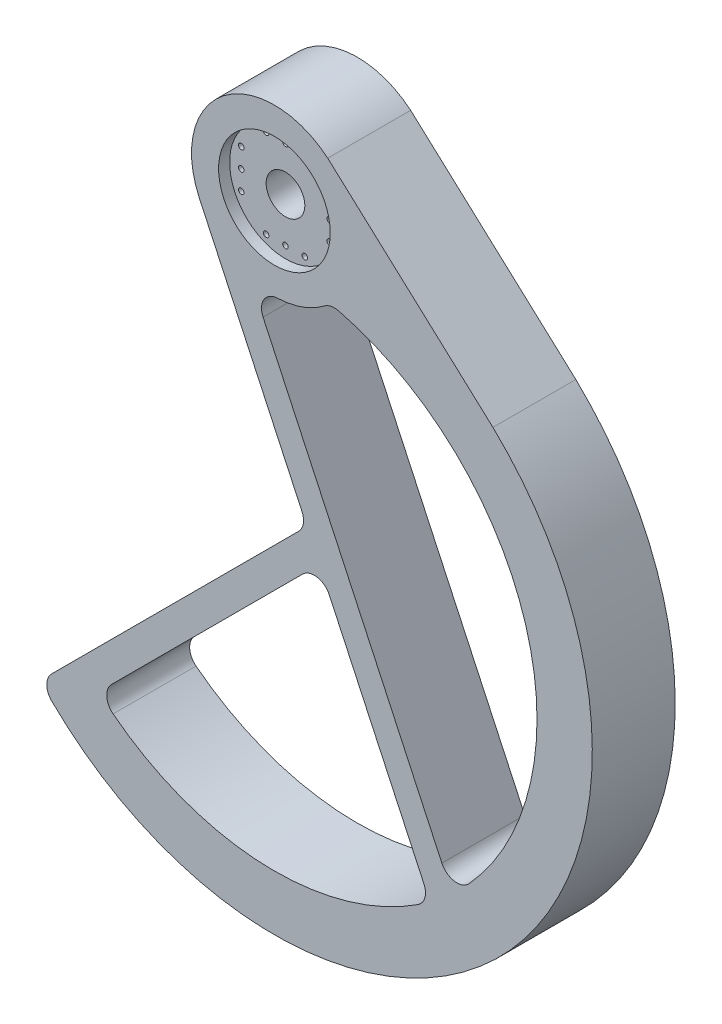
SolidWorks part; units mm, degrees
material "ABS"
ref_plane "正面" through (0, 0, 0) normal (0, 0, 1) x (1, 0, 0)
ref_plane "平面" through (0, 0, 0) normal (0, 1, 0) x (1, 0, 0)
ref_plane "右側面" through (0, 0, 0) normal (1, 0, 0) x (0, 0, -1)
sketch "ｽｹｯﾁ1" plane through (0, 0, 0) normal (0, 0, 1) x (1, 0, 0)
  line L1 (9.9336, 0.7043) -> (27.0462, -35.9938)
  line L2 (9.6418, 68.9907) -> (39.5241, 41.7624)
  line L4 (4.3888, 7.9244) -> (-40.3035, -36.7679)
  line L5 (5.0933, 1.5578) -> (-29.4572, -32.9928)
  line L6 (-13.5946, 51.1607) -> (4.9864, 11.3135)
  line L7 (30.2877, -31.1143) -> (-2.0547, 38.2444)
  arc A0 (-40.2839, -41.0299) -> (37.9168, 43.2269) centre (0, 0) ccw
  arc A1 (-29.1788, -37.4813) -> (25.9673, -39.7737) centre (0, 0) ccw
  arc A2 (0.5535, 42.5102) -> (9.0577, 45.5435) centre (0, 57.5) ccw
  arc A3 (35.2318, -31.8586) -> (11.602, 46.0613) centre (0, 0) ccw
  arc A4 (10.5469, 68.1659) -> (-13.5946, 51.1607) centre (0, 57.5) ccw
  arc A5 (-40.3035, -36.7679) -> (-40.2839, -41.0299) centre (-38.1821, -38.8893) ccw
  arc A6 (-29.4572, -32.9928) -> (-29.1788, -37.4813) centre (-27.3359, -35.1141) ccw
  arc A7 (27.0462, -35.9938) -> (25.9673, -39.7737) centre (24.3273, -37.2617) cw
  arc A8 (5.0933, 1.5578) -> (9.9336, 0.7043) centre (7.2147, -0.5635) cw
  arc A9 (35.2318, -31.8586) -> (30.2877, -31.1143) centre (33.0067, -29.8464) cw
  arc A10 (4.9864, 11.3135) -> (4.3888, 7.9244) centre (2.2675, 10.0457) cw
  arc A11 (-2.0547, 38.2444) -> (0.5535, 42.5102) centre (0.6642, 39.5123) cw
  arc A12 (11.602, 46.0613) -> (9.0577, 45.5435) centre (10.8692, 43.1522) ccw
  point P24 (8.1229, 4.5874)
  dimension "D1" = 3
  dimension "D2" = 3
  dimension "D3" = 3
  dimension "D4" = 3
  dimension "D5" = 3
  dimension "D6" = 3
  dimension "D7" = 3
  dimension "D8" = 3
extrude "ﾎﾞｽ - 押し出し1" add sketch "ｽｹｯﾁ1" along normal blind 15 contours L6 A10 L4 A5 A0 L2 A4 A12 A3 A9 L7 A11 A2 L5 A8 L1 A7 A1 A6
sketch "ｽｹｯﾁ6" plane through (0, 0, 15) normal (0, 0, 1) x (1, 0, 0)
  circle A0 centre (0, 57.5) radius 3.5
extrude "ｶｯﾄ - 押し出し2" cut sketch "ｽｹｯﾁ6" against normal blind 15
sketch "ｽｹｯﾁ7" plane through (0, 0, 15) normal (0, 0, 1) x (1, 0, 0)
  circle A0 centre (0, 57.5) radius 10.1
extrude "ｶｯﾄ - 押し出し3" cut sketch "ｽｹｯﾁ7" against normal blind 2
sketch "ｽｹｯﾁ8" plane through (0, 0, 13) normal (0, 0, 1) x (1, 0, 0)
  line L0 (0, 65.5) -> (-3.5, 65.5) construction
  line L1 (0, 57.5) -> (0, 65.5) construction
  line L2 (0, 65.5) -> (3.5, 65.5) construction
  circle A0 centre (-3.5, 65.5) radius 0.5
  circle A1 centre (0, 65.5) radius 0.5
  circle A2 centre (3.5, 65.5) radius 0.5
  circle A3 centre (8, 57.5) radius 0.5
  circle A4 centre (8, 61) radius 0.5
  circle A5 centre (8, 54) radius 0.5
  circle A6 centre (0, 49.5) radius 0.5
  circle A7 centre (3.5, 49.5) radius 0.5
  circle A8 centre (-3.5, 49.5) radius 0.5
  circle A9 centre (-8, 57.5) radius 0.5
  circle A10 centre (-8, 54) radius 0.5
  circle A11 centre (-8, 61) radius 0.5
  point P25 (0, 57.5)
extrude "ｶｯﾄ - 押し出し4" cut sketch "ｽｹｯﾁ8" against normal blind 3
